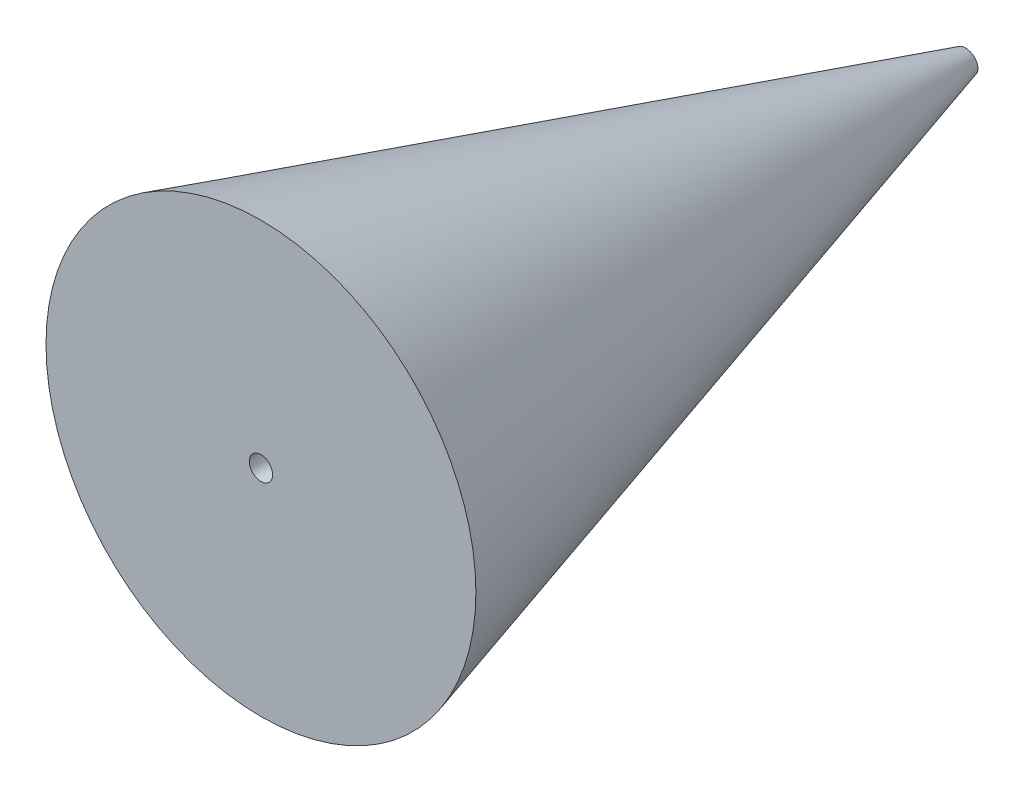
SolidWorks part; units mm, degrees
ref_plane "Front Plane" through (0, 0, 0) normal (0, 0, 1) x (1, 0, 0)
ref_plane "Top Plane" through (0, 0, 0) normal (0, 1, 0) x (1, 0, 0)
ref_plane "Right Plane" through (0, 0, 0) normal (1, 0, 0) x (0, 0, -1)
sketch "Sketch1" plane through (0, 0, 0) normal (0, 0, 1) x (1, 0, 0)
  circle A0 centre (0.0172, 0.069) radius 3.175
  dimension "D1" = 6.35
sketch "Sketch2" plane through (0, 0, 0) normal (0, 1, 0) x (1, 0, 0)
  line L0 (0.0172, 0) -> (0.0172, 203.2)
  line L1 (-3.1578, 0) -> (3.1922, 0) construction
  line L2 (0.0172, 0) -> (58.5825, 0)
  line L3 (58.5825, 0) -> (0.0172, 203.2)
revolve "Revolve1" add sketch "Sketch2" angle 360 about L0
extrude "Cut-Extrude1" cut sketch "Sketch1" against normal blind 203.2 and the other way through all contours A0
